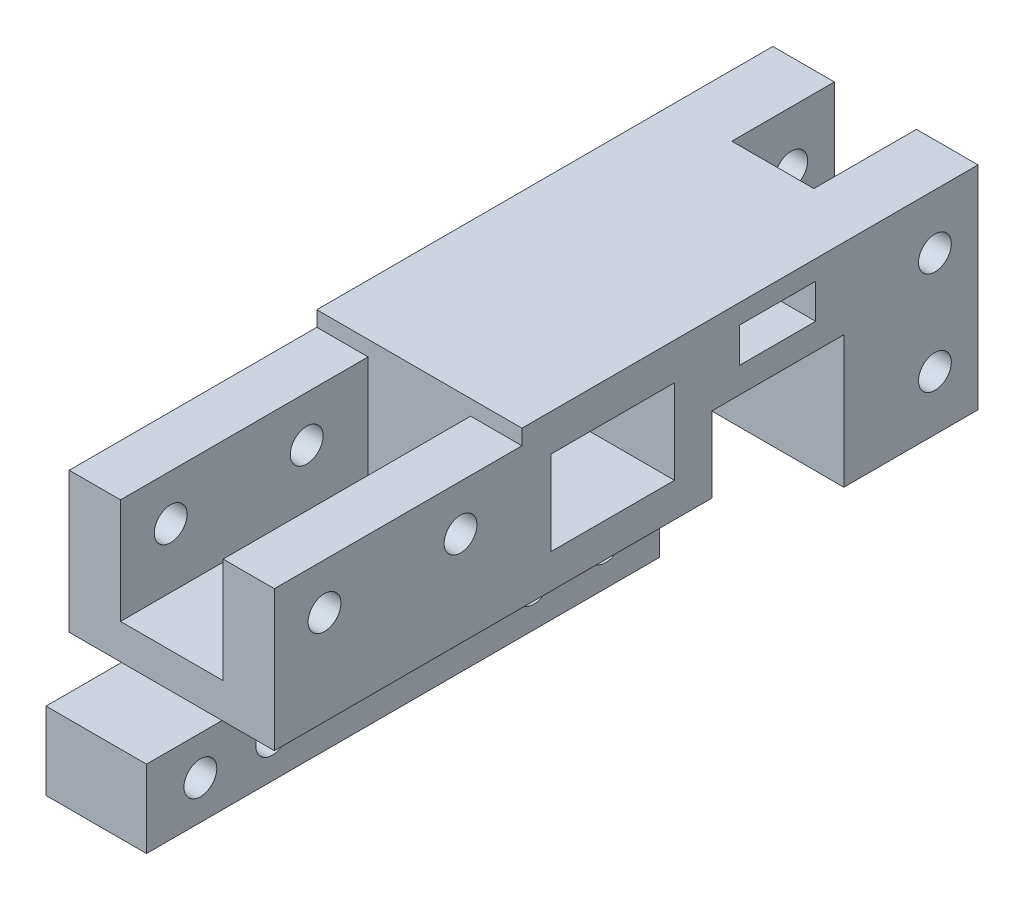
SolidWorks part; units mm, degrees
ref_plane "前视基准面" through (0, 0, 0) normal (0, 0, 1) x (1, 0, 0)
ref_plane "上视基准面" through (0, 0, 0) normal (0, 1, 0) x (1, 0, 0)
ref_plane "右视基准面" through (0, 0, 0) normal (1, 0, 0) x (0, 0, -1)
sketch "草图2" plane through (0, 0, 0) normal (1, 0, 0) x (0, 0, -1)
  line L0 (7, 0) -> (32.5, 0) construction
  line L2 (44.75, 3.775) -> (-5.25, 3.775)
  line L3 (44.75, 3.775) -> (44.75, -3.775)
  line L4 (44.75, -3.775) -> (-5.25, -3.775)
  line L5 (-5.25, 3.775) -> (-5.25, -3.775)
  line L6 (44.75, 3.775) -> (-5.25, -3.775) construction
  line L7 (44.75, -3.775) -> (-5.25, 3.775) construction
  circle A0 centre (0, 0) radius 1.6
  circle A1 centre (7, 0) radius 1.6
  circle A2 centre (32.5, 0) radius 1.6
  circle A3 centre (39.5, 0) radius 1.6
  point P9 (19.75, 0)
extrude "凸台-拉伸1" add sketch "草图2" along normal mid plane 9.8
sketch "草图3" plane through (0, 0, 0) normal (1, 0, 0) x (0, 0, -1)
  line L0 (7, 13) -> (20.26, 13) construction
  line L1 (2.1144, 3.775) -> (2.1144, 17.4551)
  line L2 (44.75, 3.775) -> (-5.25, 3.775) construction
  line L3 (2.1144, 17.4551) -> (26.2473, 17.4551)
  line L4 (26.2473, 17.4551) -> (26.2473, 3.775)
  line L5 (26.2473, 3.775) -> (2.1144, 3.775)
  circle A0 centre (7, 13) radius 1.6
  circle A1 centre (20.26, 13) radius 1.6
  point P0 (7, 0)
  point P6 (13.63, 13)
extrude "凸台-拉伸2" add sketch "草图3" along normal mid plane 20
sketch "草图4" plane through (0, 0, -2.1144) normal (0, 0, 1) x (1, 0, 0)
  line L0 (10, 17.4551) -> (-10, 17.4551) construction
  line L1 (5, 7.1905) -> (-5, 7.1905)
  line L2 (5, 7.1905) -> (5, 17.4551)
  line L3 (5, 17.4551) -> (-5, 17.4551)
  line L4 (-5, 7.1905) -> (-5, 17.4551)
  line L5 (5, 7.1905) -> (-5, 17.4551) construction
  line L6 (5, 17.4551) -> (-5, 7.1905) construction
  point P0 (0, 12.3228)
extrude "切除-拉伸1" cut sketch "草图4" against normal through all
sketch "草图6" plane through (0, 0, 0) normal (1, 0, 0) x (0, 0, -1)
  line L0 (66.5, 3.6) -> (66.5, 13.6) construction
  line L1 (66.5, 8.6) -> (56.4496, 8.6) construction
  line L2 (70.7021, -1.739) -> (57.626, -1.739)
  line L3 (70.7021, -1.739) -> (70.7021, 18.939)
  line L4 (70.7021, 18.939) -> (57.626, 18.939)
  line L5 (57.626, -1.739) -> (57.626, 18.939)
  line L6 (70.7021, -1.739) -> (57.626, 18.939) construction
  line L7 (70.7021, 18.939) -> (57.626, -1.739) construction
  circle A0 centre (66.5, 3.6) radius 1.6
  circle A1 centre (66.5, 13.6) radius 1.6
  point P4 (66.5, 8.6)
  point P9 (64.1641, 8.6)
  point P10 (0, 0)
  point P11 (0, 0)
  point P14 (0, 0)
  point P15 (64.1641, 8.6)
extrude "凸台-拉伸4" add sketch "草图6" along normal mid plane 20 separate body
sketch "草图7" plane through (0, 0, -70.7021) normal (0, 0, 1) x (1, 0, 0)
  line L0 (10, 18.939) -> (-10, 18.939) construction
  line L1 (-4, 18.939) -> (4, 18.939)
  line L2 (-4, 18.939) -> (-4, -1.739)
  line L3 (-4, -1.739) -> (4, -1.739)
  line L4 (4, 18.939) -> (4, -1.739)
  line L5 (10, -1.739) -> (-10, -1.739) construction
  point P8 (0, 0)
  point P9 (0, 0)
extrude "切除-拉伸2" cut sketch "草图7" along normal blind 10
sketch "草图8" plane through (0, 0, 0) normal (1, 0, 0) x (0, 0, -1)
  line L0 (26.2473, 3.775) -> (26.2473, 17.4551) construction
  line L1 (57.626, 18.939) -> (26.2473, 18.939)
  line L2 (57.626, 18.939) -> (57.626, 11.1399)
  line L3 (57.626, 11.1399) -> (44.75, 11.1399)
  line L4 (26.2473, 18.939) -> (26.2473, 11.1399)
  line L7 (26.2473, 11.1399) -> (26.2473, 3.775)
  line L8 (26.2473, 3.775) -> (44.75, 3.775)
  line L9 (44.75, 11.1399) -> (44.75, 3.775)
extrude "凸台-拉伸5" add sketch "草图8" along normal mid plane 20
sketch "草图9" plane through (10, 0, 0) normal (1, 0, 0) x (0, 0, -1)
  line L1 (29.0864, 15.338) -> (41.1155, 15.338)
  line L2 (29.0864, 15.338) -> (29.0864, 7.1034)
  line L3 (29.0864, 7.1034) -> (41.1155, 7.1034)
  line L4 (41.1155, 15.338) -> (41.1155, 7.1034)
  line L5 (29.0864, 15.338) -> (41.1155, 7.1034) construction
  line L6 (29.0864, 7.1034) -> (41.1155, 15.338) construction
  line L7 (54.8802, 13.6426) -> (47.4529, 13.6426)
  line L8 (54.8802, 13.6426) -> (54.8802, 17.0334)
  line L9 (54.8802, 17.0334) -> (47.4529, 17.0334)
  line L10 (47.4529, 13.6426) -> (47.4529, 17.0334)
  line L11 (54.8802, 13.6426) -> (47.4529, 17.0334) construction
  line L12 (54.8802, 17.0334) -> (47.4529, 13.6426) construction
  point P0 (35.101, 11.2207)
  point P5 (51.1666, 15.338)
  point P8 (51.1666, 15.338)
extrude "切除-拉伸3" cut sketch "草图9" against normal through all
